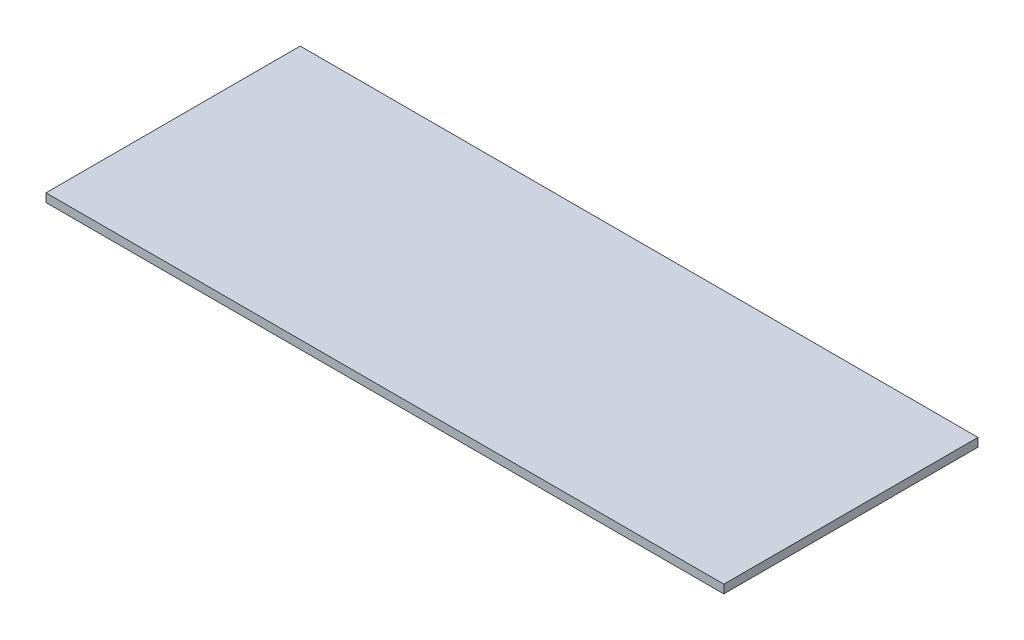
SolidWorks part; units mm, degrees
ref_plane "Front" through (0, 0, 0) normal (0, 0, 1) x (1, 0, 0)
ref_plane "Top" through (0, 0, 0) normal (0, 1, 0) x (1, 0, 0)
ref_plane "Right" through (0, 0, 0) normal (1, 0, 0) x (0, 0, -1)
sketch "草图1" plane through (0, 0, 0) normal (0, 1, 0) x (1, 0, 0)
  line L1 (0, 0) -> (203.2, 0)
  line L2 (0, 0) -> (0, -76.2)
  line L3 (0, -76.2) -> (203.2, -76.2)
  line L4 (203.2, 0) -> (203.2, -76.2)
  dimension "D1" = 203.2
  dimension "D2" = 76.2
extrude "凸台-拉伸1" add sketch "草图1" along normal blind 2.54
